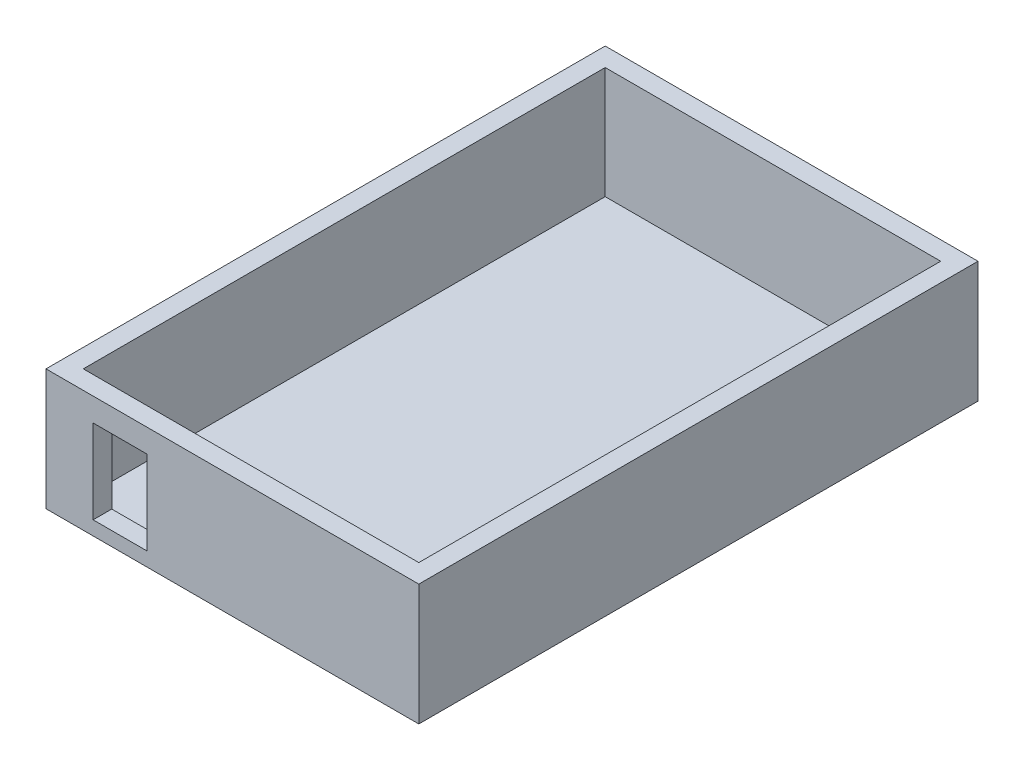
SolidWorks part; units mm, degrees
ref_plane "Front Plane" through (0, 0, 0) normal (0, 0, 1) x (1, 0, 0)
ref_plane "Top Plane" through (0, 0, 0) normal (0, 1, 0) x (1, 0, 0)
ref_plane "Right Plane" through (0, 0, 0) normal (1, 0, 0) x (0, 0, -1)
sketch "Sketch1" plane through (0, 0, 0) normal (0, 1, 0) x (1, 0, 0)
  line L1 (-9899.8331, 14942.404) -> (100.1669, 14942.404)
  line L2 (-9899.8331, 14942.404) -> (-9899.8331, -57.596)
  line L3 (-9899.8331, -57.596) -> (100.1669, -57.596)
  line L4 (100.1669, 14942.404) -> (100.1669, -57.596)
  line L5 (-9899.8331, 14942.404) -> (100.1669, -57.596) construction
  line L6 (-9899.8331, -57.596) -> (100.1669, 14942.404) construction
  point P0 (-4899.8331, 7442.404)
  dimension "D1" = 10000
  dimension "D2" = 15000
extrude "Base" add sketch "Sketch1" along normal blind 250
sketch "Sketch3" plane through (0, 250, 0) normal (0, 1, 0) x (1, 0, 0)
  line L1 (-9899.8331, 442.404) -> (100.1669, 442.404)
  line L2 (-9899.8331, 442.404) -> (-9899.8331, -57.596)
  line L3 (-9899.8331, -57.596) -> (100.1669, -57.596)
  line L4 (100.1669, 442.404) -> (100.1669, -57.596)
  line L5 (-9899.8331, 442.404) -> (100.1669, -57.596) construction
  line L6 (-9899.8331, -57.596) -> (100.1669, 442.404) construction
  line L7 (100.1669, -57.596) -> (100.1669, 14942.404) construction
  line L8 (-9899.8331, -57.596) -> (100.1669, -57.596) construction
  point P0 (-4899.8331, 192.404)
  point P9 (-4899.8331, -57.596)
  dimension "D1" = 10000
  dimension "D2" = 5000
  dimension "D3" = 500
  dimension "D4" = 250
extrude "Wall_1" add sketch "Sketch3" along normal blind 3000
sketch "Sketch4" plane through (0, 250, 0) normal (0, 1, 0) x (1, 0, 0)
  line L0 (-9899.8331, -57.596) -> (100.1669, -57.596) construction
  line L1 (-9899.8331, 14442.404) -> (-9399.8331, 14442.404)
  line L2 (-9899.8331, 14442.404) -> (-9899.8331, 442.404)
  line L3 (-9899.8331, 442.404) -> (-9399.8331, 442.404)
  line L4 (-9399.8331, 14442.404) -> (-9399.8331, 442.404)
  line L5 (-9899.8331, 14442.404) -> (-9399.8331, 442.404) construction
  line L6 (-9899.8331, 442.404) -> (-9399.8331, 14442.404) construction
  line L7 (-9899.8331, 14942.404) -> (-9899.8331, 442.404) construction
  point P0 (-9649.8331, 7442.404)
  dimension "D1" = 14000
  dimension "D2" = 500
  dimension "D3" = 7500
  dimension "D4" = 250
extrude "Wall_2" add sketch "Sketch4" along normal blind 3000
sketch "Sketch5" plane through (0, 250, 0) normal (0, 1, 0) x (1, 0, 0)
  line L0 (-9899.8331, -57.596) -> (100.1669, -57.596) construction
  line L1 (-399.8331, 14442.404) -> (100.1669, 14442.404)
  line L2 (-399.8331, 14442.404) -> (-399.8331, 442.404)
  line L3 (-399.8331, 442.404) -> (100.1669, 442.404)
  line L4 (100.1669, 14442.404) -> (100.1669, 442.404)
  line L5 (-399.8331, 14442.404) -> (100.1669, 442.404) construction
  line L6 (-399.8331, 442.404) -> (100.1669, 14442.404) construction
  line L7 (100.1669, -57.596) -> (100.1669, 14942.404) construction
  point P0 (-149.8331, 7442.404)
  dimension "D1" = 14000
  dimension "D2" = 7500
  dimension "D3" = 250
extrude "Wall_3" add sketch "Sketch5" along normal blind 3000 contours L2 L3 L4 L1
sketch "Sketch6" plane through (0, 250, 0) normal (0, 1, 0) x (1, 0, 0)
  line L0 (-9899.8331, 14942.404) -> (-9899.8331, 14442.404) construction
  line L1 (-9899.8331, 14942.404) -> (100.1669, 14942.404)
  line L2 (-9899.8331, 14942.404) -> (-9899.8331, 14442.404)
  line L3 (-9899.8331, 14442.404) -> (100.1669, 14442.404)
  line L4 (100.1669, 14942.404) -> (100.1669, 14442.404)
  line L5 (-9899.8331, 14942.404) -> (100.1669, 14442.404) construction
  line L6 (-9899.8331, 14442.404) -> (100.1669, 14942.404) construction
  line L8 (100.1669, 14942.404) -> (-9899.8331, 14942.404) construction
  point P0 (-4899.8331, 14692.404)
  dimension "D1" = 10000
  dimension "D2" = 5000
  dimension "D3" = 500
  dimension "D4" = 250
extrude "Wall_4" add sketch "Sketch6" along normal blind 3000
sketch "Sketch8" plane through (0, 0, 57.596) normal (0, 0, 1) x (1, 0, 0)
  line L0 (-9899.8331, 0) -> (100.1669, 0) construction
  line L1 (-8636.053, 2625) -> (-7188.2678, 2625)
  line L2 (-8636.053, 2625) -> (-8636.053, 375)
  line L3 (-8636.053, 375) -> (-7188.2678, 375)
  line L4 (-7188.2678, 2625) -> (-7188.2678, 375)
  line L5 (-8636.053, 2625) -> (-7188.2678, 375) construction
  line L6 (-8636.053, 375) -> (-7188.2678, 2625) construction
  point P0 (-7912.1604, 1500)
  dimension "D1" = 2250
  dimension "D2" = 1500
extrude "Cut-Extrude1" cut sketch "Sketch8" against normal blind 2000
